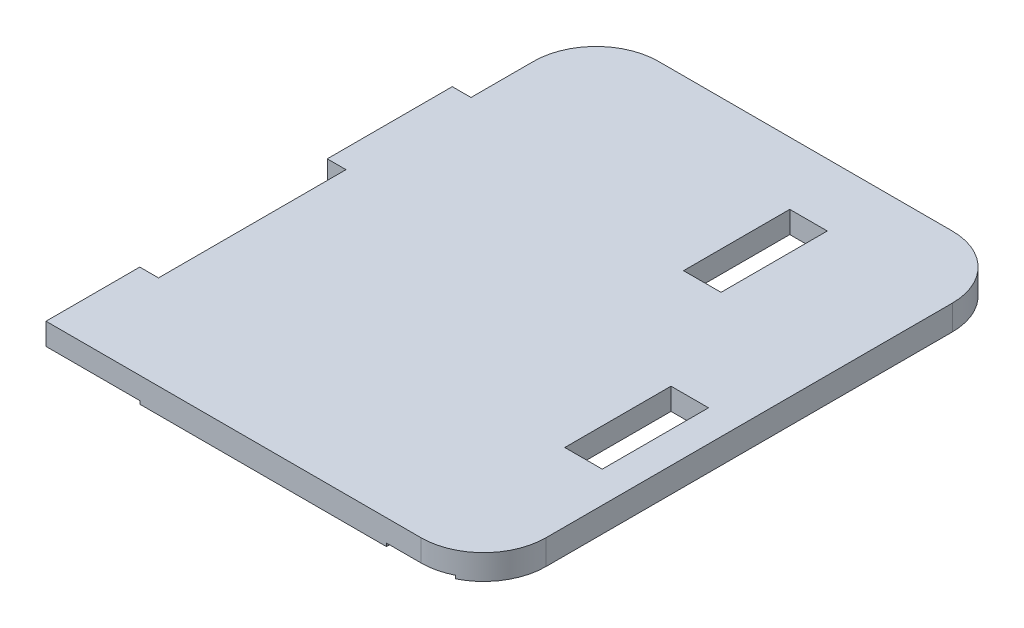
SolidWorks part; units mm, degrees
material "PBT General Purpose"
ref_plane "Front Plane" through (0, 0, 0) normal (0, 0, 1) x (1, 0, 0)
ref_plane "Top Plane" through (0, 0, 0) normal (0, 1, 0) x (1, 0, 0)
ref_plane "Right Plane" through (0, 0, 0) normal (1, 0, 0) x (0, 0, -1)
sketch "Sketch1" plane through (0, 0, 0) normal (0, 1, 0) x (1, 0, 0)
  line L0 (0, 0) -> (7, 0)
  line L5 (7, 0) -> (7, 8.5)
  line L6 (7, 8.5) -> (0.3, 8.5)
  line L7 (0.3, 8.5) -> (0.3, 6.5)
  line L8 (0.3, 6.5) -> (0, 6.5)
  line L9 (0, 6.5) -> (0, 4.5)
  line L10 (0, 4.5) -> (0.3, 4.5)
  line L11 (0.3, 4.5) -> (0.3, 1.5)
  line L12 (0.3, 1.5) -> (0, 1.5)
  line L13 (0, 1.5) -> (0, 0)
  line L15 (4.4, 7.5) -> (5, 7.5)
  line L16 (4.4, 7.5) -> (4.4, 5.8)
  line L17 (4.4, 5.8) -> (5, 5.8)
  line L18 (5, 7.5) -> (5, 5.8)
  line L19 (5.9, 2.4) -> (6.5, 2.4)
  line L20 (5.9, 2.4) -> (5.9, 4.1)
  line L21 (5.9, 4.1) -> (6.5, 4.1)
  line L22 (6.5, 2.4) -> (6.5, 4.1)
  dimension "D1" = 2
  dimension "D2" = 1.5
  dimension "D3" = 3
  dimension "D4" = 2
  dimension "D5" = 5.6
  dimension "D7" = 1.7
  dimension "D8" = 0.6
  dimension "D9" = 0.3
  dimension "D10" = 4.1
  dimension "D11" = 0.6
  dimension "D12" = 1.7
  dimension "D13" = 1
  dimension "D14" = 7
  dimension "D6" = 4.4
extrude "Boss-Extrude1" add sketch "Sketch1" along normal blind 0.4
fillet "Fillet2" radius 1 3 edges at (7, 0.2, 0) (7, 0.2, -8.5) (0.3, 0.2, -8.5)
sketch "Sketch2" plane through (0, 0, 0) normal (0, -1, 0) x (1, 0, 0)
  line L0 (5.9, -2.4) -> (5.9, -5.1) construction
  line L1 (6.4482, -2.4) -> (6.4482, -5.1)
  line L2 (5.4482, -2.4) -> (5.4482, -4.7094)
  line L3 (4.4, -5.8) -> (4.4, -8.5) construction
  line L4 (6, -8.5) -> (1.3, -8.5) construction
  line L5 (4.9, -5.8) -> (4.9, -8.5)
  line L6 (3.9, -5.8) -> (3.9, -8.5)
  line L7 (5.9792, -5.6424) -> (4.9, -5.8)
  line L8 (5.4482, -4.7094) -> (4.3278, -4.873)
  line L9 (6.4482, -2.4) -> (6.4482, 0)
  line L10 (0, 0) -> (6, 0) construction
  line L11 (6.4482, 0) -> (5.4482, 0)
  line L12 (5.4482, 0) -> (5.4482, -2.4)
  line L13 (3.9, -5.8) -> (3.9, -5.3677)
  line L14 (1.5, -8.5) -> (0, -8.5)
  line L15 (1.5, -8.5) -> (1.5, 0)
  line L16 (1.5, 0) -> (0, 0)
  line L17 (0, -8.5) -> (0, 0)
  arc A1 (5.9792, -5.6424) -> (6.4482, -5.1) centre (5.9, -5.1) ccw
  arc A3 (3.9, -8.5) -> (4.9, -8.5) centre (4.4, -8.5) ccw
  arc A4 (4.3278, -4.873) -> (3.9, -5.3677) centre (4.4, -5.3677) ccw
  point P3 (5.9, -3.75)
  point P8 (4.4, -7.15)
  dimension "D2" = 0.5482
  dimension "D3" = 1
  dimension "D6" = 0.5
  dimension "D1" = 2.7
  dimension "D4" = 1
  dimension "D5" = 1
  dimension "D7" = 1.5
extrude "Cut-Extrude1" cut sketch "Sketch2" against normal blind 0.05
equation "\"t\"= 0.3'thickness of the sheets"
equation "\"FlexJoint\"= 0.15'Width of flextures"
equation "\"FoldJoint\"= 0.4'Width of folding joints"
equation "\"AssembleAngle\"= 90'Angle of assembly parts"
equation "\"D9@Sketch1\"=\"t\""
